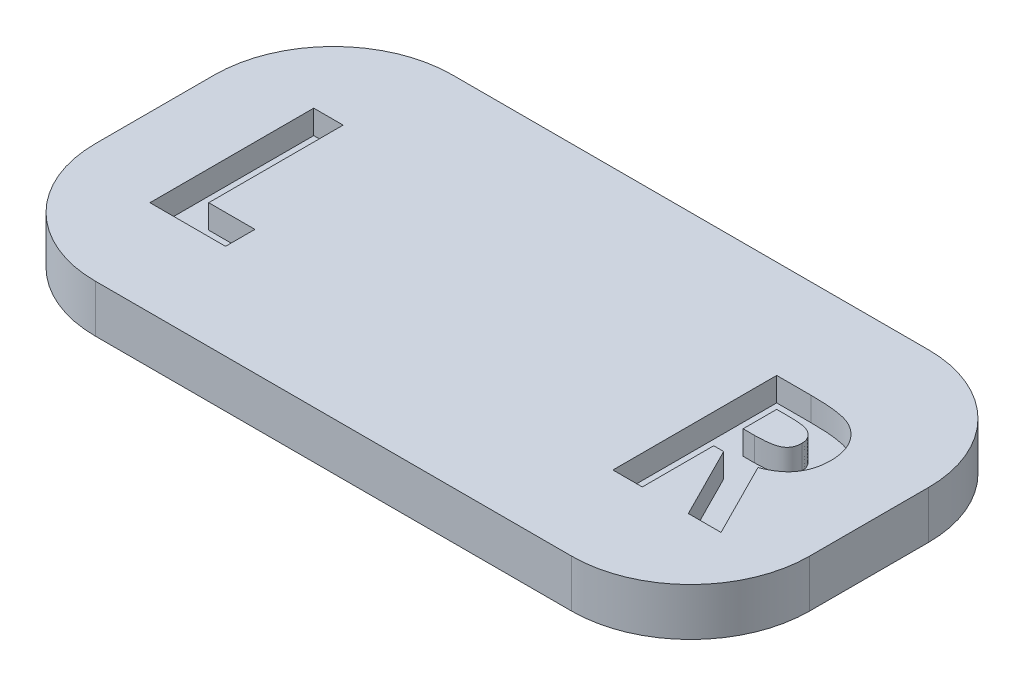
SolidWorks part; units mm, degrees
ref_plane "Front Plane" through (0, 0, 0) normal (0, 0, 1) x (1, 0, 0)
ref_plane "Top Plane" through (0, 0, 0) normal (0, 1, 0) x (1, 0, 0)
ref_plane "Right Plane" through (0, 0, 0) normal (1, 0, 0) x (0, 0, -1)
sketch "Sketch1" plane through (0, 0, 0) normal (0, 1, 0) x (1, 0, 0)
  line L1 (-15, 7.5) -> (15, 7.5)
  line L2 (-15, 7.5) -> (-15, -7.5)
  line L3 (-15, -7.5) -> (15, -7.5)
  line L4 (15, 7.5) -> (15, -7.5)
  point P4 (-15, 0)
  point P7 (0, 7.5)
  dimension "D1" = 15
  dimension "D2" = 30
extrude "Boss-Extrude1" add sketch "Sketch1" along normal blind 2
fillet "Fillet1" radius 5 4 edges at (-15, 1, -7.5) (15, 1, -7.5) (15, 1, 7.5) (-15, 1, 7.5)
sketch "Sketch3" plane through (0, 2, 0) normal (0, 1, 0) x (1, 0, 0)
  line L0 (-12.5, -3.5) -> (12.5, -3.5) construction
  line L2 (-10, -7.5) -> (10, -7.5) construction
  line L3 (-15, 2.5) -> (-15, -2.5) construction
  text T0 "<b>L</b>" font "Century Gothic" height in points 26
  text T1 "<b>R</b>" font "Century Gothic" height in points 26
  dimension "D1" = 25
  dimension "D2" = 4
  dimension "D3" = 2.5
extrude "Cut-Extrude1" cut sketch "Sketch3" against normal blind 1
